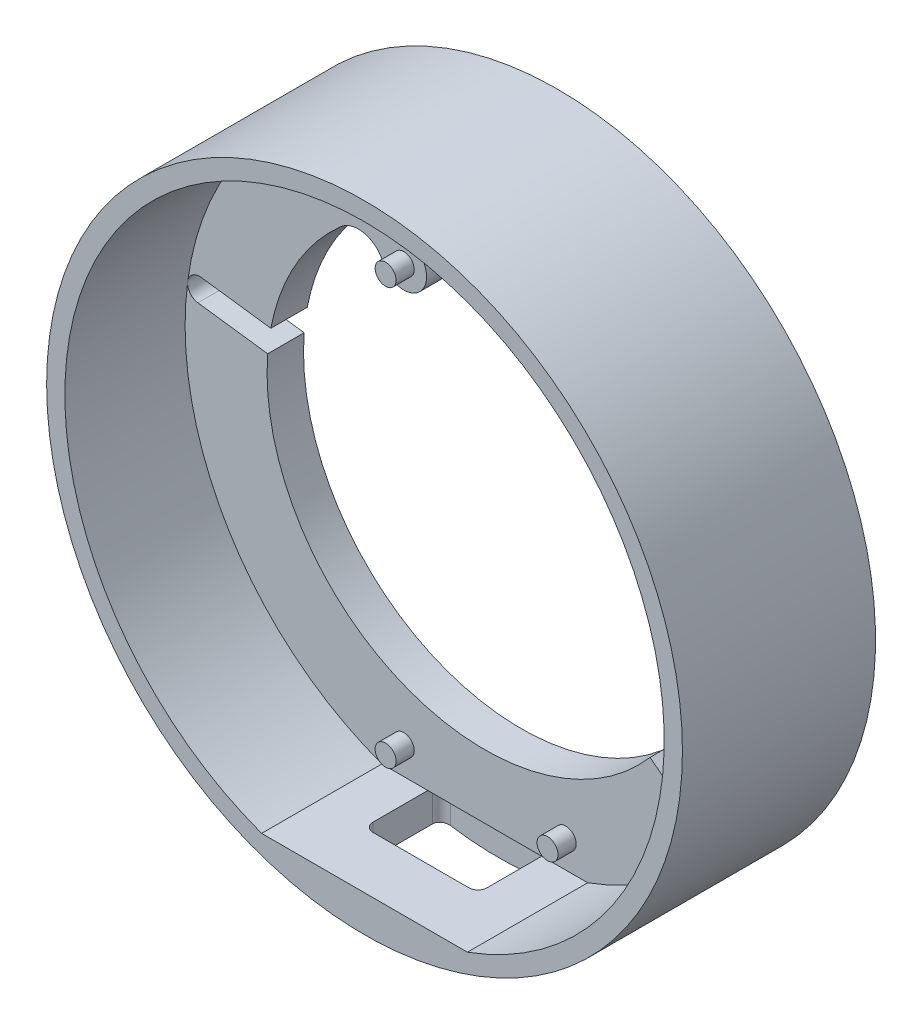
SolidWorks part; units mm, degrees
ref_plane "Plan de face" through (0, 0, 0) normal (0, 0, 1) x (1, 0, 0)
ref_plane "Plan de dessus" through (0, 0, 0) normal (0, 1, 0) x (1, 0, 0)
ref_plane "Plan de droite" through (0, 0, 0) normal (1, 0, 0) x (0, 0, -1)
sketch "Esquisse_carte_affichage" plane through (0, 0, 0) normal (0, 0, 1) x (1, 0, 0)
  circle A0 centre (19.25, 25.1) radius 0.5
  circle A1 centre (25.07, -19.23) radius 0.5
  circle A2 centre (29.18, 12.09) radius 0.5
  circle A3 centre (31.32, -4.14) radius 0.5
  circle A4 centre (-29.21, -12.07) radius 0.5
  circle A5 centre (-31.32, 4.14) radius 0.5
  circle A6 centre (-26.4935, -7.4094) radius 0.25
  circle A7 centre (-23.6728, -14.0139) radius 0.25
  circle A8 centre (-19.2392, -19.6637) radius 0.25
  circle A9 centre (-13.4943, -23.973) radius 0.25
  circle A10 centre (-6.8298, -26.6487) radius 0.25
  circle A11 centre (0.3, -27.5085) radius 0.25
  circle A12 centre (7.4094, -26.4935) radius 0.25
  circle A13 centre (14.0139, -23.6728) radius 0.25
  circle A14 centre (19.6637, -19.2392) radius 0.25
  circle A15 centre (23.973, -13.4943) radius 0.25
  circle A16 centre (26.6487, -6.8298) radius 0.25
  circle A17 centre (27.5085, 0.3) radius 0.25
  circle A18 centre (26.4935, 7.4094) radius 0.25
  circle A19 centre (23.6728, 14.0139) radius 0.25
  circle A20 centre (19.2392, 19.6637) radius 0.25
  circle A21 centre (13.4943, 23.973) radius 0.25
  circle A22 centre (6.8298, 26.6487) radius 0.25
  circle A23 centre (-0.3, 27.5085) radius 0.25
  circle A24 centre (-7.4094, 26.4935) radius 0.25
  circle A25 centre (-14.0139, 23.6728) radius 0.25
  circle A26 centre (-19.6637, 19.2392) radius 0.25
  circle A27 centre (-23.973, 13.4943) radius 0.25
  circle A28 centre (-26.6487, 6.8298) radius 0.25
  circle A29 centre (-27.5085, -0.3) radius 0.25
  circle A30 centre (-30.2, -7.1) radius 0.25
  circle A31 centre (-26.5986, -15.746) radius 0.25
  circle A32 centre (-28.1305, -7.8674) radius 0.25
  circle A33 centre (-21.6169, -22.0937) radius 0.25
  circle A34 centre (-25.1358, -14.8801) radius 0.25
  circle A35 centre (-15.162, -26.9359) radius 0.25
  circle A36 centre (-20.428, -20.8785) radius 0.25
  circle A37 centre (-7.6738, -29.9423) radius 0.25
  circle A38 centre (-14.3281, -25.4544) radius 0.25
  circle A39 centre (0.3371, -30.9082) radius 0.25
  circle A40 centre (-7.252, -28.2956) radius 0.25
  circle A41 centre (8.3254, -29.7678) radius 0.25
  circle A42 centre (0.3185, -29.2082) radius 0.25
  circle A43 centre (15.746, -26.5986) radius 0.25
  circle A44 centre (7.8674, -28.1305) radius 0.25
  circle A45 centre (22.0937, -21.6169) radius 0.25
  circle A46 centre (14.8801, -25.1358) radius 0.25
  circle A47 centre (26.9359, -15.162) radius 0.25
  circle A48 centre (20.8785, -20.428) radius 0.25
  circle A49 centre (29.9423, -7.6738) radius 0.25
  circle A50 centre (25.4544, -14.3281) radius 0.25
  circle A51 centre (30.9082, 0.3371) radius 0.25
  circle A52 centre (28.2956, -7.252) radius 0.25
  circle A53 centre (29.7678, 8.3254) radius 0.25
  circle A54 centre (29.2082, 0.3185) radius 0.25
  circle A55 centre (26.5986, 15.746) radius 0.25
  circle A56 centre (28.1305, 7.8674) radius 0.25
  circle A57 centre (21.6169, 22.0937) radius 0.25
  circle A58 centre (25.1358, 14.8801) radius 0.25
  circle A59 centre (15.162, 26.9359) radius 0.25
  circle A60 centre (20.428, 20.8785) radius 0.25
  circle A61 centre (7.6738, 29.9423) radius 0.25
  circle A62 centre (14.3281, 25.4544) radius 0.25
  circle A63 centre (-0.3371, 30.9082) radius 0.25
  circle A64 centre (7.252, 28.2956) radius 0.25
  circle A65 centre (-8.3254, 29.7678) radius 0.25
  circle A66 centre (-0.3185, 29.2082) radius 0.25
  circle A67 centre (-15.746, 26.5986) radius 0.25
  circle A68 centre (-7.8674, 28.1305) radius 0.25
  circle A69 centre (-22.0937, 21.6169) radius 0.25
  circle A70 centre (-14.8801, 25.1358) radius 0.25
  circle A71 centre (-26.9359, 15.162) radius 0.25
  circle A72 centre (-20.8785, 20.428) radius 0.25
  circle A73 centre (-29.9423, 7.6738) radius 0.25
  circle A74 centre (-25.4544, 14.3281) radius 0.25
  circle A75 centre (-30.9082, -0.3371) radius 0.25
  circle A76 centre (-28.2956, 7.252) radius 0.25
  circle A77 centre (0, 0) radius 26.162
  circle A78 centre (0, 0) radius 32.766
  dimension "D1" = 65.532
  dimension "D2" = 52.324
sketch "Esquisse_carte_mère" plane through (0, 0, 0) normal (0, 0, 1) x (1, 0, 0)
  line L0 (-11.3435, -28.5174) -> (-11.0897, -29.13)
  line L1 (-11.0897, -29.13) -> (-10.6861, -29.6561)
  line L2 (-10.6861, -29.6561) -> (-10.16, -30.0597)
  line L3 (-10.16, -30.0597) -> (-9.5474, -30.3135)
  line L4 (-9.5474, -30.3135) -> (-8.89, -30.4)
  line L5 (-8.89, -30.4) -> (-2.413, -30.4)
  line L6 (-2.413, -30.4) -> (-1.905, -29.892)
  line L7 (-1.905, -29.892) -> (1.905, -29.892)
  line L8 (1.905, -29.892) -> (2.413, -30.4)
  line L9 (2.413, -30.4) -> (8.89, -30.4)
  line L10 (8.89, -30.4) -> (9.5474, -30.3135)
  line L11 (9.5474, -30.3135) -> (10.16, -30.0597)
  line L12 (10.16, -30.0597) -> (10.6861, -29.6561)
  line L13 (10.6861, -29.6561) -> (11.0897, -29.13)
  line L14 (11.0897, -29.13) -> (11.3435, -28.5174)
  line L15 (11.3435, -28.5174) -> (11.43, -27.86)
  line L16 (11.43, -27.86) -> (11.43, 17.86)
  line L17 (11.43, 17.86) -> (11.3435, 18.5174)
  line L18 (11.3435, 18.5174) -> (11.0897, 19.13)
  line L19 (11.0897, 19.13) -> (10.6861, 19.6561)
  line L20 (10.6861, 19.6561) -> (10.16, 20.0597)
  line L21 (10.16, 20.0597) -> (9.5474, 20.3135)
  line L22 (9.5474, 20.3135) -> (8.89, 20.4)
  line L23 (8.89, 20.4) -> (-8.89, 20.4)
  line L24 (-8.89, 20.4) -> (-9.5474, 20.3135)
  line L25 (-9.5474, 20.3135) -> (-10.16, 20.0597)
  line L26 (-10.16, 20.0597) -> (-10.6861, 19.6561)
  line L27 (-10.6861, 19.6561) -> (-11.0897, 19.13)
  line L28 (-11.0897, 19.13) -> (-11.3435, 18.5174)
  line L29 (-11.3435, 18.5174) -> (-11.43, 17.86)
  line L30 (-11.43, 17.86) -> (-11.43, -27.86)
  line L31 (-11.43, -27.86) -> (-11.3435, -28.5174)
  line L32 (8.9522, -28.0199) -> (-18113.3609, 46572.2136) construction
  line L33 (-8.9266, -27.9541) -> (18113.3865, 46572.2795) construction
  circle A0 centre (-3.3, -25.05) radius 0.4
  circle A1 centre (3.3, -25.05) radius 0.4
  circle A2 centre (-3.6, -27.86) radius 0.45
  circle A3 centre (3.6, -27.86) radius 0.45
  circle A4 centre (10.16, 14.05) radius 0.5
  circle A5 centre (10.16, 11.51) radius 0.5
  circle A6 centre (10.16, 8.97) radius 0.5
  circle A7 centre (10.16, 6.43) radius 0.5
  circle A8 centre (10.16, 3.89) radius 0.5
  circle A9 centre (10.16, 1.35) radius 0.5
  circle A10 centre (10.16, -1.19) radius 0.5
  circle A11 centre (10.16, -3.73) radius 0.5
  circle A12 centre (10.16, -6.27) radius 0.5
  circle A13 centre (10.16, -8.81) radius 0.5
  circle A14 centre (10.16, -11.35) radius 0.5
  circle A15 centre (10.16, -13.89) radius 0.5
  circle A16 centre (-10.16, -24.05) radius 0.5
  circle A17 centre (-10.16, -21.51) radius 0.5
  circle A18 centre (-10.16, -18.97) radius 0.5
  circle A19 centre (-10.16, -16.43) radius 0.5
  circle A20 centre (-10.16, -13.89) radius 0.5
  circle A21 centre (-10.16, -11.35) radius 0.5
  circle A22 centre (-10.16, -8.81) radius 0.5
  circle A23 centre (-10.16, -6.27) radius 0.5
  circle A24 centre (-10.16, -3.73) radius 0.5
  circle A25 centre (-10.16, -1.19) radius 0.5
  circle A26 centre (-10.16, 1.35) radius 0.5
  circle A27 centre (-10.16, 3.89) radius 0.5
  circle A28 centre (-10.16, 6.43) radius 0.5
  circle A29 centre (-10.16, 8.97) radius 0.5
  circle A30 centre (-10.16, 11.51) radius 0.5
  circle A31 centre (-10.16, 14.05) radius 0.5
  circle A32 centre (-8.89, -27.86) radius 1.25
  circle A33 centre (8.89, -27.86) radius 1.25
  circle A34 centre (-8.89, 17.86) radius 1.25
  circle A35 centre (8.89, 17.86) radius 1.25
  circle A36 centre (-1.95, -25.955) radius 0.35
  circle A37 centre (1.95, -25.955) radius 0.35
  circle A38 centre (-2.2, 15.706) radius 0.45
  circle A39 centre (3.048, -15.795) radius 0.25
  circle A40 centre (1.016, -20.875) radius 0.25
  circle A41 centre (-6.223, -9.826) radius 0.25
  circle A42 centre (-6.096, -16.43) radius 0.25
  circle A43 centre (7.3914, -2.0028) radius 0.25
  circle A44 centre (7.366, -18.462) radius 0.25
  circle A45 centre (-1.905, 12.018) radius 0.25
  circle A46 centre (1.905, 9.224) radius 0.25
  circle A47 centre (-5.715, -21.129) radius 0.25
  circle A48 centre (-4.064, -1.571) radius 0.25
  circle A49 centre (-8.509, -22.78) radius 0.25
  circle A50 centre (0.2286, -14.5758) radius 0.25
  circle A51 centre (0.508, 7.446) radius 0.25
  circle A52 centre (0.635, 8.589) radius 0.25
  circle A53 centre (-7.112, 0.334) radius 0.25
  circle A54 centre (4.953, -15.795) radius 0.25
  circle A55 centre (0, 10.494) radius 0.25
  circle A56 centre (-4.191, -16.43) radius 0.25
  circle A57 centre (-0.889, -17.573) radius 0.25
  circle A58 centre (5.842, -10.715) radius 0.25
  circle A59 centre (2.159, -17.446) radius 0.25
  circle A60 centre (0, -27.987) radius 0.25
  circle A61 centre (-1.397, 4.271) radius 0.25
  circle A62 centre (-5.207, 1.985) radius 0.25
  circle A63 centre (-0.381, -6.651) radius 0.25
  circle A64 centre (6.858, 8.462) radius 0.25
  circle A65 centre (5.207, 3.128) radius 0.25
  circle A66 centre (2.667, 4.525) radius 0.25
  circle A67 centre (5.08, 11.764) radius 0.25
  circle A68 centre (0, 14.431) radius 0.25
  circle A69 centre (-1.778, 8.716) radius 0.25
  circle A70 centre (-2.921, 4.271) radius 0.25
  circle A71 centre (-5.588, 3.128) radius 0.25
  circle A72 centre (-1.905, -19.732) radius 0.25
  circle A73 centre (-5.842, -8.683) radius 0.25
  circle A74 centre (-3.048, -20.113) radius 0.25
  circle A75 centre (-6.604, -7.667) radius 0.25
  circle A76 centre (-5.207, -10.842) radius 0.25
  circle A77 centre (10.668, -26.082) radius 0.25
  circle A78 centre (5.969, -4.365) radius 0.25
  circle A79 centre (5.08, -9.191) radius 0.25
  circle A80 centre (-3.81, -3.349) radius 0.25
  circle A81 centre (-4.953, -9.699) radius 0.25
  circle A82 centre (3.048, 6.43) radius 0.25
  circle A83 centre (5.969, -3.222) radius 0.25
  circle A84 centre (6.858, -7.667) radius 0.25
  circle A85 centre (6.477, 6.303) radius 0.25
  circle A86 centre (-1.27, 10.367) radius 0.25
  circle A87 centre (-1.0922, -0.1994) radius 0.25
  circle A88 centre (0.508, -0.428) radius 0.25
  circle A89 centre (4.318, -17.065) radius 0.25
  circle A90 centre (1.524, 4.144) radius 0.25
  circle A91 centre (-2.921, -1.444) radius 0.25
  circle A92 centre (3.302, -10.08) radius 0.25
  circle A93 centre (-3.81, -10.08) radius 0.25
  circle A94 centre (-5.08, -6.778) radius 0.25
  point P222 (0, -5)
  dimension "D5" = 2.5
  dimension "D1" = 2.54
  dimension "D2" = 2.54
  dimension "D3" = 2.54
  dimension "D4" = 2.54
sketch "Esquisse_support" plane through (0, 0, 0) normal (0, 0, 1) x (1, 0, 0)
  line L0 (0, 0) -> (0, -50000) construction
  line L1 (0, 0) -> (-31.32, 4.14) construction
  line L2 (0, 0) -> (19.25, 25.1) construction
  line L3 (0, 0) -> (25.07, -19.23) construction
  line L4 (25.07, -19.23) -> (30456.2807, 39653.7005) construction
  line L5 (19.25, 25.1) -> (39694.4792, -30403.1136) construction
  line L6 (-31.32, 4.14) -> (6520.8813, 49572.9675) construction
  line L7 (-31.1487, 5.4363) -> (-23.4871, 4.4235)
  line L8 (-31.4913, 2.8437) -> (-23.8298, 1.831)
  line L9 (18.2437, 25.8718) -> (13.5179, 19.7098)
  line L10 (20.2563, 24.3282) -> (15.5305, 18.1663)
  line L11 (25.8637, -18.1952) -> (19.7291, -13.4897)
  line L12 (24.2763, -20.2648) -> (18.1417, -15.5592)
  line L13 (-8.89, 17.86) -> (46591.3436, 18140.1731) construction
  line L14 (8.89, 17.86) -> (-46591.3436, 18140.1731) construction
  line L15 (11.22, 16.9539) -> (13.5179, 19.7098)
  line L16 (72498.2044, -186428.9542) -> (-90602.6131, 232973.148) construction
  line L17 (-72498.1788, -186428.8884) -> (90602.6387, 232973.2138) construction
  circle A0 centre (0, 0) radius 32.9 construction
  circle A1 centre (0, 0) radius 34.9
  arc A2 (-32.6163, 4.3113) -> (-31.4913, 2.8437) centre (-31.32, 4.14) ccw
  arc A3 (-32.6163, 4.3113) -> (-31.1487, 5.4363) centre (-31.32, 4.14) cw
  arc A4 (20.0218, 26.1063) -> (18.2437, 25.8718) centre (19.25, 25.1) ccw
  arc A5 (20.0218, 26.1063) -> (20.2563, 24.3282) centre (19.25, 25.1) cw
  arc A6 (26.1048, -20.0237) -> (25.8637, -18.1952) centre (25.07, -19.23) ccw
  arc A7 (26.1048, -20.0237) -> (24.2763, -20.2648) centre (25.07, -19.23) cw
  arc A8 (-23.4871, 4.4235) -> (13.5179, 19.7098) centre (0, 0) cw construction
  arc A9 (-23.8298, 1.831) -> (18.1417, -15.5592) centre (0, 0) ccw
  arc A10 (19.7291, -13.4897) -> (15.5305, 18.1663) centre (0, 0) ccw
  arc A11 (-6.56, 18.7661) -> (-11.22, 16.9539) centre (-8.89, 17.86) cw
  arc A12 (6.56, 18.7661) -> (11.22, 16.9539) centre (8.89, 17.86) ccw
  arc A13 (-6.56, 18.7661) -> (-4.1838, 23.531) centre (-3.28, 20.1053) cw
  arc A14 (6.56, 18.7661) -> (4.1838, 23.531) centre (3.28, 20.1053) ccw
  arc A15 (-11.22, 16.9539) -> (-15.8818, 17.86) centre (-13.8724, 15.7529) ccw
  arc A16 (-23.4871, 4.4235) -> (-15.8818, 17.86) centre (0, 0) cw
  arc A17 (-4.1838, 23.531) -> (4.1838, 23.531) centre (0, 0) cw
  point P37 (-4.1838, 23.531)
  dimension "D1" = 65.8
  dimension "D2" = 69.8
  dimension "D12" = 2.5
  dimension "D13" = 2.5
  dimension "D3" = 90
  dimension "D4" = 90
  dimension "D5" = 90
  dimension "D7" = 90
  dimension "D8" = 90
  dimension "D9" = 90
  dimension "D10" = 90
  dimension "D11" = 90
extrude "Boss.-Extru.1" add sketch "Esquisse_support" along normal blind 4 contours A1 A13 A17 A14 A12 L15 L9 A4 A5 L10 A10 L11 A6 A7 L12 A9 L8 A2 A3 L7 A16 A15 A11
sketch "Esquisse6" plane through (0, 0, 4) normal (0, 0, 1) x (1, 0, 0)
  line L0 (0, 0) -> (0, -50000) construction
  circle A0 centre (-8.89, 17.86) radius 1.15
  circle A1 centre (-8.89, -27.86) radius 1.15
  circle A2 centre (8.89, -27.86) radius 1.15
  circle A3 centre (8.89, 17.86) radius 1.15
  dimension "D1" = 2.3
  dimension "D2" = 2.3
extrude "Boss.-Extru.2" add sketch "Esquisse6" along normal blind 2
sketch "Esquisse7" plane through (0, 0, 0) normal (0, 0, -1) x (-1, 0, 0)
  circle A0 centre (0, 0) radius 34.9
  circle A1 centre (0, 0) radius 32.9
extrude "Boss.-Extru.3" add sketch "Esquisse7" along normal blind 4
sketch "Esquisse8" plane through (0, 0, 4) normal (0, 0, 1) x (1, 0, 0)
  line L0 (0, 0) -> (0, -50000) construction
  line L1 (-11.296, -30.9) -> (11.296, -30.9)
  line L2 (-8.89, -30.4) -> (-2.413, -30.4) construction
  circle A0 centre (0, 0) radius 34.9
  circle A1 centre (0, 0) radius 32.9 construction
  arc A2 (-11.296, -30.9) -> (11.296, -30.9) centre (0, 0) cw
  point P9 (0, -30.9)
  circle M5 centre (0, 0) radius 34.9
  dimension "D2" = 0.5
extrude "Boss.-Extru.5" add sketch "Esquisse8" along normal blind 13.2 contours A2 L1 M5
sketch "Ouverture_USB" plane through (0, -30.9, 0) normal (0, 1, 0) x (1, 0, 0)
  line L0 (0, -16.2747) -> (0, 5.3613) construction
  line L2 (-5.25, -11) -> (5.25, -11)
  line L3 (-6.25, -10) -> (-6.25, -3.5)
  line L4 (-5.25, -2.5) -> (5.25, -2.5)
  line L5 (6.25, -10) -> (6.25, -3.5)
  arc A0 (6.25, -10) -> (5.25, -11) centre (5.25, -10) cw
  arc A1 (6.25, -3.5) -> (5.25, -2.5) centre (5.25, -3.5) ccw
  arc A2 (-5.25, -2.5) -> (-6.25, -3.5) centre (-5.25, -3.5) ccw
  arc A3 (-6.25, -10) -> (-5.25, -11) centre (-5.25, -10) ccw
  dimension "D4" = 1
  dimension "D1" = 8.5
  dimension "D2" = 12.5
  dimension "D3" = 2.5
extrude "Enlèv. mat.-Extru.1" cut sketch "Ouverture_USB" against normal blind 10
